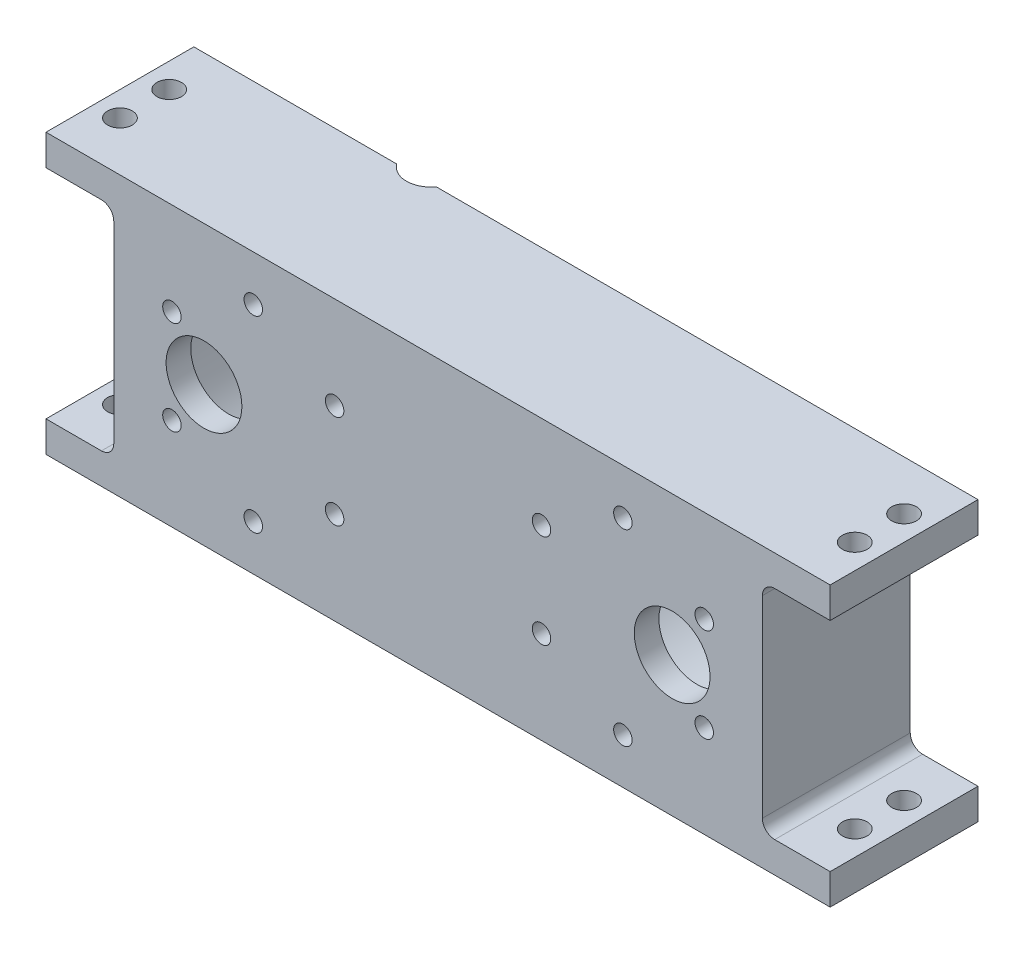
SolidWorks part; units mm, degrees
ref_plane "Front Plane" through (0, 0, 0) normal (0, 0, 1) x (1, 0, 0)
ref_plane "Top Plane" through (0, 0, 0) normal (0, 1, 0) x (1, 0, 0)
ref_plane "Right Plane" through (0, 0, 0) normal (1, 0, 0) x (0, 0, -1)
sketch "Sketch1" plane through (0, 0, 0) normal (0, 0, 1) x (1, 0, 0)
  line L0 (60, 0) -> (0, 0) construction
  line L6 (82.65, 22.65) -> (-22.65, 22.65)
  line L7 (82.65, 22.65) -> (82.65, -22.65)
  line L8 (82.65, -22.65) -> (-22.65, -22.65)
  line L9 (-22.65, 22.65) -> (-22.65, -22.65)
  line L10 (82.65, 22.65) -> (-22.65, -22.65) construction
  line L11 (82.65, -22.65) -> (-22.65, 22.65) construction
  circle A1 centre (0, 0) radius 18.65
  circle A4 centre (60, 0) radius 18.65
  point P3 (30, 0)
  dimension "D2" = 4
  dimension "D3" = 37.3
  dimension "D4" = 60
  dimension "D1" = 4
extrude "Boss-Extrude1" add sketch "Sketch1" against normal blind 20
sketch "Sketch2" plane through (0, 0, 0) normal (0, 0, 1) x (1, 0, 0)
  line L1 (0, 0) -> (0, 15.25) construction
  line L8 (30, 22.65) -> (30, -22.65) construction
  line L9 (82.65, 22.65) -> (-22.65, 22.65) construction
  line L10 (-22.65, -22.65) -> (82.65, -22.65) construction
  line L12 (-22.65, 22.65) -> (82.65, 22.65)
  line L13 (-22.65, 22.65) -> (-22.65, -22.65)
  line L14 (-22.65, -22.65) -> (82.65, -22.65)
  line L15 (82.65, 22.65) -> (82.65, -22.65)
  line L16 (-22.65, 22.65) -> (82.65, -22.65) construction
  line L17 (-22.65, -22.65) -> (82.65, 22.65) construction
  circle A1 centre (-8, 0) radius 6.15
  circle A2 centre (0, 15.25) radius 1.5
  circle A3 centre (13.2069, 7.625) radius 1.5
  circle A4 centre (13.2069, -7.625) radius 1.5
  circle A5 centre (0, -15.25) radius 1.5
  circle A6 centre (-13.2069, -7.625) radius 1.5
  circle A7 centre (-13.2069, 7.625) radius 1.5
  circle A9 centre (73.2069, -7.625) radius 1.5
  circle A10 centre (60, -15.25) radius 1.5
  circle A11 centre (46.7931, -7.625) radius 1.5
  circle A12 centre (46.7931, 7.625) radius 1.5
  circle A13 centre (60, 15.25) radius 1.5
  circle A14 centre (73.2069, 7.625) radius 1.5
  circle A15 centre (68, 0) radius 6.15
  point P19 (0, 0)
  point P41 (30, 0)
  dimension "D1" = 12.3
  dimension "D4" = 3
  dimension "D2" = 8
  dimension "D3" = 15.25
  dimension "D5" = 6
extrude "Boss-Extrude2" add sketch "Sketch2" along normal blind 4
sketch "Sketch3" plane through (0, -22.65, 0) normal (0, -1, 0) x (1, 0, 0)
  line L0 (-22.65, -20) -> (82.65, -20) construction
  line L1 (-22.65, 4) -> (-33.65, 4)
  line L2 (-22.65, 4) -> (-22.65, -20)
  line L3 (-22.65, -20) -> (-33.65, -20)
  line L4 (-33.65, 4) -> (-33.65, -20)
  line L5 (-29.65, 4) -> (-29.65, -4) construction
  line L6 (-29.65, -4) -> (-29.65, -12) construction
  line L7 (-29.65, -12) -> (-29.65, -20) construction
  line L8 (30, 4) -> (30, -20) construction
  line L9 (-22.65, 4) -> (82.65, 4) construction
  line L10 (82.65, -20) -> (93.65, -20)
  line L11 (93.65, 4) -> (93.65, -20)
  line L12 (82.65, 4) -> (93.65, 4)
  line L13 (82.65, 4) -> (82.65, -20)
  circle A0 centre (-29.65, -4) radius 2
  circle A1 centre (-29.65, -12) radius 2
  circle A2 centre (89.65, -4) radius 2
  circle A3 centre (89.65, -12) radius 2
  dimension "D1" = 4
  dimension "D2" = 5
  dimension "D3" = 2
extrude "Boss-Extrude3" add sketch "Sketch3" against normal blind 5
fillet "Fillet1" radius 2 2 edges at (-22.65, -17.65, -8) (82.65, -17.65, -8)
sketch "Sketch4" plane through (0, 22.65, 0) normal (0, 1, 0) x (1, 0, 0)
  line L1 (-22.65, 20) -> (-33.65, 20)
  line L2 (-22.65, 20) -> (-22.65, -4)
  line L3 (-22.65, -4) -> (-33.65, -4)
  line L4 (-33.65, 20) -> (-33.65, -4)
  line L5 (82.65, 20) -> (93.65, 20)
  line L6 (82.65, 20) -> (82.65, -4)
  line L7 (82.65, -4) -> (93.65, -4)
  line L8 (93.65, 20) -> (93.65, -4)
  circle A0 centre (-29.65, 12) radius 2
  circle A1 centre (-29.65, 4) radius 2
  circle A2 centre (89.65, 12) radius 2
  circle A3 centre (89.65, 4) radius 2
extrude "Boss-Extrude4" add sketch "Sketch4" against normal blind 5
fillet "Fillet2" radius 2 2 edges at (-22.65, 17.65, -8) (82.65, 17.65, -8)
sketch "Sketch6" plane through (0, -22.65, 0) normal (0, -1, 0) x (1, 0, 0)
  circle A0 centre (2.5, -22.3686) radius 4
  circle A1 centre (2.5, -117.6314) radius 4
  dimension "D1" = 8
extrude "Cut-Extrude1" cut sketch "Sketch6" against normal blind 20
sketch "Sketch7" plane through (0, -22.65, 0) normal (0, -1, 0) x (1, 0, 0)
  circle A0 centre (2.5, -22.3686) radius 4.0472
extrude "Cut-Extrude2" cut sketch "Sketch7" against normal blind 20
sketch "Sketch8" plane through (0, 22.65, 0) normal (0, 1, 0) x (1, 0, 0)
  circle A0 centre (2.5, 22.3686) radius 4
  dimension "D1" = 8
extrude "Cut-Extrude3" cut sketch "Sketch8" against normal blind 20
